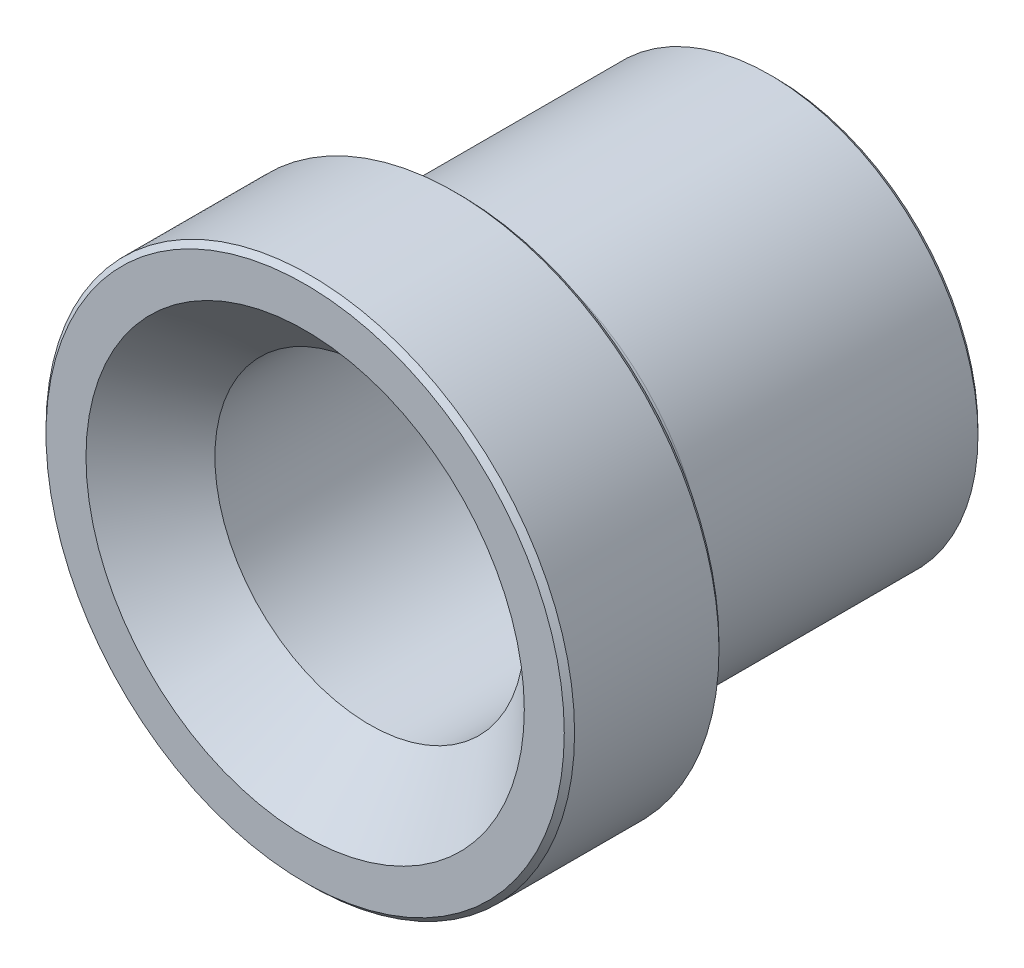
SolidWorks part; units mm, degrees
ref_plane "Alzado" through (0, 0, 0) normal (0, 0, 1) x (1, 0, 0)
ref_plane "Planta" through (0, 0, 0) normal (0, 1, 0) x (1, 0, 0)
ref_plane "Vista lateral" through (0, 0, 0) normal (1, 0, 0) x (0, 0, -1)
sketch "Croquis1" plane through (0, 0, 0) normal (1, 0, 0) x (0, 0, -1)
  line L0 (0, 8.5) -> (0, 10.05)
  line L1 (0.2, 10.25) -> (5.8, 10.25)
  line L2 (6, 10.05) -> (6, 9.565)
  line L3 (7.5, 8.065) -> (18.03, 8.065)
  line L4 (18.23, 7.865) -> (18.23, 6.2)
  line L5 (18.03, 6) -> (2.5, 6)
  line L6 (0, 0) -> (11.343, 0) construction
  line L7 (5.8, 10.25) -> (6, 10.05)
  line L8 (0, 10.05) -> (0.2, 10.25)
  line L9 (18.03, 8.065) -> (18.23, 7.865)
  line L11 (18.23, 6.2) -> (18.03, 6)
  line L12 (0, 8.5) -> (2.5, 6)
  arc A0 (6, 9.565) -> (7.5, 8.065) centre (7.5, 9.565) ccw
  point P1 (0, 10.25)
  point P4 (6, 10.25)
  point P6 (18.23, 8.065)
  point P7 (18.23, 6)
  point P8 (0, 6)
  point P13 (6, 8.065)
  dimension "D6" = 1.5
  dimension "D1" = 8.065
  dimension "D2" = 6
  dimension "D3" = 10.25
  dimension "D4" = 6
  dimension "D5" = 12.23
  dimension "D7" = 45
  dimension "D8" = 2.5
revolve "Revolución1" add sketch "Croquis1" angle 360 about L6
sketch "Croquis2" plane through (0, 0, 0) normal (0, 1, 0) x (1, 0, 0)
  line L0 (0, 0) -> (0, 18.23) construction
  line L1 (7.865, 18.23) -> (-7.865, 18.23) construction
  line L3 (2.5, 18.23) -> (-2.5, 18.23)
  line L4 (2.5, 18.23) -> (2.5, 13.23)
  line L5 (2.5, 13.23) -> (-2.5, 13.23)
  line L6 (-2.5, 18.23) -> (-2.5, 13.23)
  point P9 (0, 13.23)
  dimension "D1" = 5
  dimension "D2" = 5
extrude "Cortar-Extruir1" cut sketch "Croquis2" against normal through all
